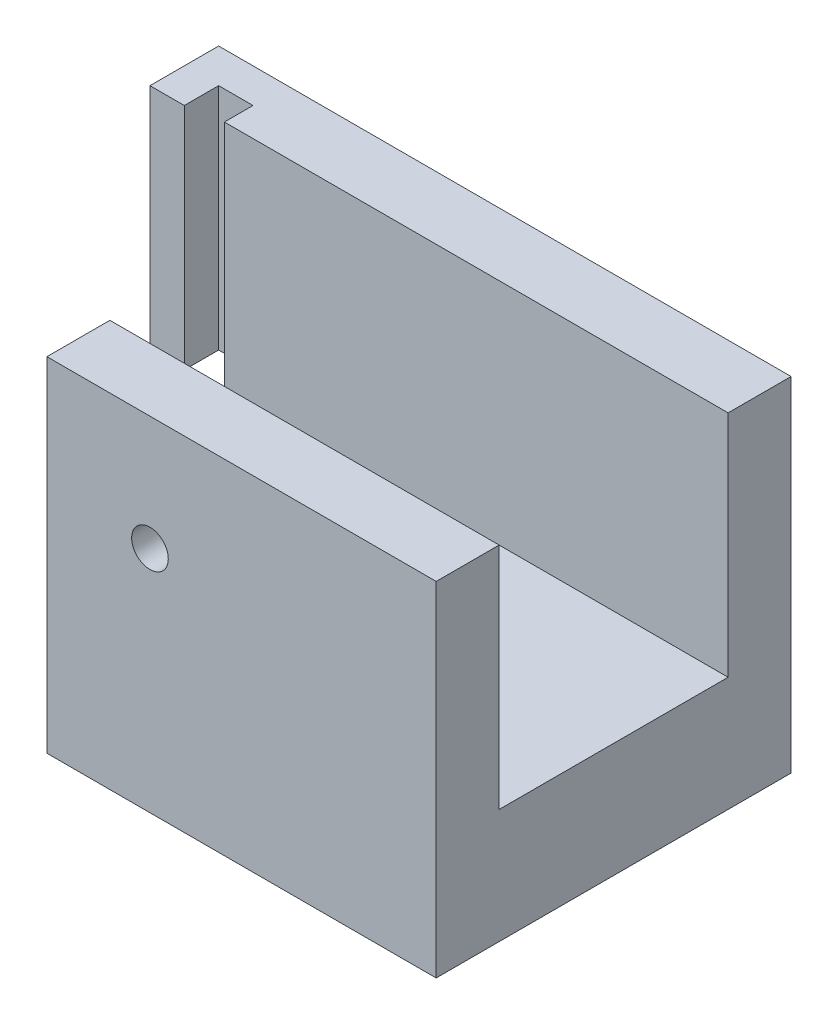
SolidWorks part; units mm, degrees
ref_plane "Front Plane" through (0, 0, 0) normal (0, 0, 1) x (1, 0, 0)
ref_plane "Top Plane" through (0, 0, 0) normal (0, 1, 0) x (1, 0, 0)
ref_plane "Right Plane" through (0, 0, 0) normal (1, 0, 0) x (0, 0, -1)
sketch "Sketch1" plane through (0, 0, 0) normal (0, 1, 0) x (1, 0, 0)
  line L0 (0, -0.5636) -> (0, -3.5636)
  line L1 (0, 11.9364) -> (25, 11.9364)
  line L2 (0, 11.9364) -> (0, 8.9364)
  line L3 (0, -3.5636) -> (25, -3.5636)
  line L4 (25, 11.9364) -> (25, -3.5636)
  line L5 (0, 8.9364) -> (1.5, 8.9364)
  line L7 (0, -0.5636) -> (1.5, -0.5636)
  line L9 (1.5, 10.4364) -> (3, 10.4364)
  line L10 (1.5, 10.4364) -> (1.5, 8.9364)
  line L11 (1.5, -2.0636) -> (3, -2.0636)
  line L12 (3, 10.4364) -> (3, -2.0636)
  line L13 (1.5, -0.5636) -> (1.5, -2.0636)
  dimension "D1" = 1.5
  dimension "D2" = 12.5
  dimension "D3" = 1.5
  dimension "D4" = 1.5
  dimension "D5" = 1.5
  dimension "D6" = 25
extrude "Boss-Extrude1" add sketch "Sketch1" along normal blind 15
sketch "Sketch2" plane through (0, 15, 0) normal (0, 1, 0) x (1, 0, 0)
  line L0 (25, -3.5636) -> (25, 11.9364) construction
  line L1 (25, 9.1864) -> (3, 9.1864)
  line L2 (25, 9.1864) -> (25, -0.8136)
  line L3 (25, -0.8136) -> (3, -0.8136)
  line L4 (3, 9.1864) -> (3, -0.8136)
  line L5 (3, 10.4364) -> (3, -2.0636) construction
  point P8 (3, 4.1864)
  point P9 (3, 4.1864)
  dimension "D1" = 10
extrude "Cut-Extrude1" cut sketch "Sketch2" against normal blind 10
sketch "Sketch3" plane through (0, 0, 3.5636) normal (0, 0, 1) x (1, 0, 0)
  line L0 (25, 5) -> (25, 15) construction
  line L1 (0, 15) -> (25, 15) construction
  point P0 (12.5, 10)
  point P4 (25, 10)
  point P8 (12.5, 15)
hole_wizard "M2x0.4 Tapped Hole1" positions "Sketch4" profile "Sketch5" tap size "M2x0.4" standard "BSI"
sketch "Sketch4" plane through (0, 0, 3.5636) normal (0, 0, 1) x (1, 0, 0)
  point P0 (12.5, 10)
sketch "Sketch5" plane through (12.5, 10, 3.5636) normal (1, 0, 0) x (0, -1, 0)
  line L0 (0, 0) -> (0, 2.75)
  line L1 (0, 2.75) -> (0.8, 2.75)
  line L2 (0.8, 2.75) -> (0.8, 0)
  line L5 (0.8, 0) -> (0, 0)
  line L11 (0, -6.35) -> (0, 107.95) construction
  dimension "Thru Tap Drill Dia." = 1.6
  dimension "Thru Tap Drill Depth" = 2.75
cosmetic thread "Hole Thread1" parameters "D2"=2
sketch "Sketch6" plane through (0, 0, 0) normal (0, -1, 0) x (1, 0, 0)
  line L0 (0, 3.5636) -> (25, 3.5636) construction
  line L1 (0, -11.9364) -> (3, -11.9364)
  line L2 (0, -11.9364) -> (0, 3.5636)
  line L3 (0, 3.5636) -> (3, 3.5636)
  line L4 (3, -11.9364) -> (3, 3.5636)
  line L5 (3, -10.4364) -> (3, 2.0636) construction
extrude "Cut-Extrude2" cut sketch "Sketch6" against normal up to surface (5 mm away) up to face at (14, 5, -4.1864)
sketch "Sketch7" plane through (0, 0, 3.5636) normal (0, 0, 1) x (1, 0, 0)
  line L1 (0, 15) -> (3, 15)
  line L2 (0, 15) -> (0, 5)
  line L3 (0, 5) -> (3, 5)
  line L4 (3, 15) -> (3, 5)
extrude "Cut-Extrude4" cut sketch "Sketch7" against normal up to surface (3 mm away) up to face at (0.75, 10, 0.5636)
sketch "Sketch8" plane through (0, 0, 3.5636) normal (0, 0, 1) x (1, 0, 0)
  line L0 (3, 15) -> (25, 15) construction
  line L1 (3, 0) -> (8, 0)
  line L2 (3, 0) -> (3, 15)
  line L3 (3, 15) -> (8, 15)
  line L4 (8, 0) -> (8, 15)
  dimension "D1" = 5
extrude "Cut-Extrude5" cut sketch "Sketch8" against normal up to surface (12.75 mm away) up to face at (14, 10, -9.1864)
